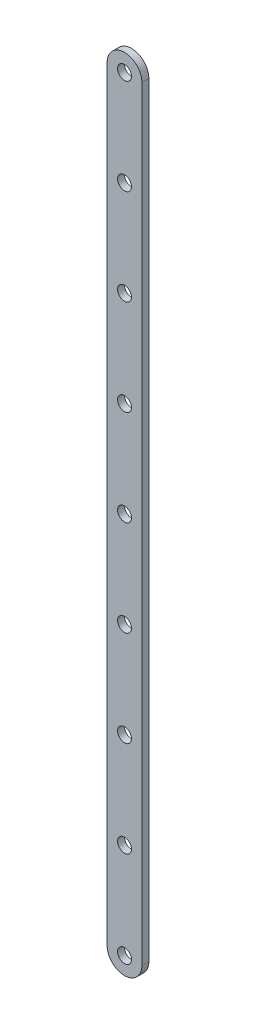
SolidWorks part; units mm, degrees
ref_plane "Front Plane" through (0, 0, 0) normal (1, 0, 0) x (0, 1, 0)
ref_plane "Top Plane" through (0, 0, 0) normal (0, 0, 1) x (0, 1, 0)
ref_plane "Right Plane" through (0, 0, 0) normal (0, 1, 0) x (-1, 0, 0)
sketch "Sketch2" plane through (0, 0, 0) normal (0, 0, 1) x (0, 1, 0)
  line L0 (-275, 12.5) -> (275, 12.5)
  line L1 (-275, -12.5) -> (275, -12.5)
  arc A0 (-275, 12.5) -> (-275, -12.5) centre (-275, 0) ccw
  arc A1 (275, 12.5) -> (275, -12.5) centre (275, 0) cw
  circle A2 centre (-275, 0) radius 5
  circle A7 centre (-206.25, 0) radius 5
  circle A8 centre (-137.5, 0) radius 5
  circle A9 centre (-68.75, 0) radius 5
  circle A10 centre (0, 0) radius 5
  circle A11 centre (68.75, 0) radius 5
  circle A12 centre (137.5, 0) radius 5
  circle A13 centre (206.25, 0) radius 5
  circle A14 centre (275, 0) radius 5
  point P6 (0, -12.5)
  point P25 (274.2333, 0)
  dimension "D1" = 25
  dimension "D3" = 10
  dimension "D4" = 9
  dimension "D2" = 550
extrude "Boss-Extrude1" add sketch "Sketch2" along normal blind 5
